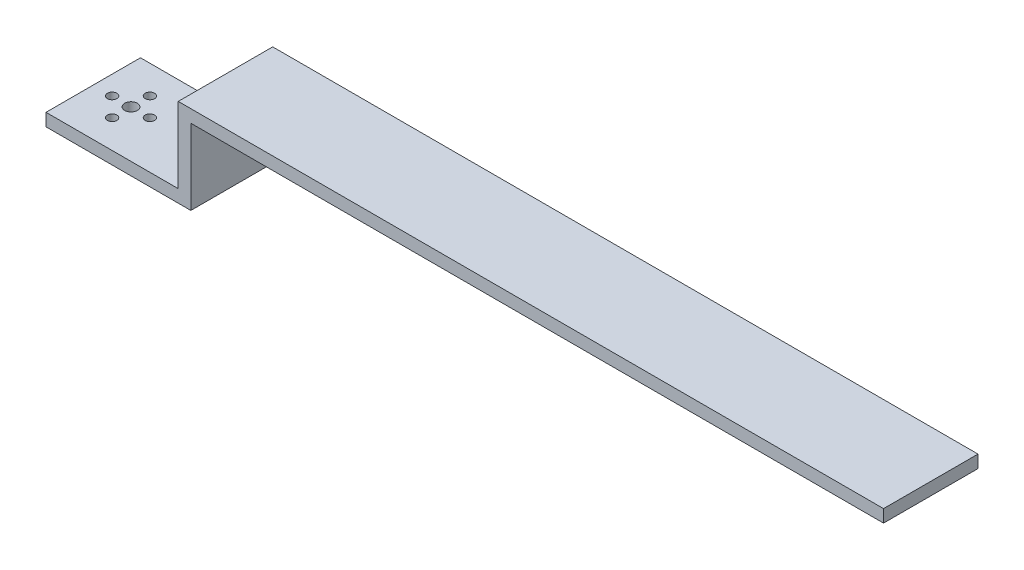
SolidWorks part; units mm, degrees
ref_plane "Front Plane" through (0, 0, 0) normal (0, 0, 1) x (1, 0, 0)
ref_plane "Top Plane" through (0, 0, 0) normal (0, 1, 0) x (1, 0, 0)
ref_plane "Right Plane" through (0, 0, 0) normal (1, 0, 0) x (0, 0, -1)
sketch "Sketch1" plane through (0, 0, 0) normal (0, 1, 0) x (1, 0, 0)
  line L0 (-23, 0) -> (23, 0) construction
  line L1 (-23, 15) -> (23, 15)
  line L2 (-23, 15) -> (-23, -15)
  line L3 (-23, -15) -> (23, -15)
  line L4 (23, 15) -> (23, -15)
  line L5 (-23, 15) -> (23, -15) construction
  line L6 (-23, -15) -> (23, 15) construction
  circle A0 centre (-11, 0) radius 6 construction
  circle A1 centre (-17, 0) radius 1.5
  circle A2 centre (-11, 6) radius 1.5
  circle A3 centre (-5, 0) radius 1.5
  circle A4 centre (-11, -6) radius 1.5
  circle A5 centre (-11, 0) radius 2
  point P0 (0, 0)
  point P9 (0, 0)
  point P22 (-11, 0)
  dimension "D3" = 12
  dimension "D4" = 12
  dimension "D5" = 3
  dimension "D6" = 4
  dimension "D7" = 4
  dimension "D1" = 30
  dimension "D2" = 46
extrude "Boss-Extrude1" add sketch "Sketch1" along normal blind 4
sketch "Sketch2" plane through (0, 4, 0) normal (0, 1, 0) x (1, 0, 0)
  line L0 (-23, -15) -> (23, -15) construction
  line L1 (23, 15) -> (19, 15)
  line L2 (23, 15) -> (23, -15)
  line L3 (23, -15) -> (19, -15)
  line L4 (19, 15) -> (19, -15)
  dimension "D1" = 4
extrude "Boss-Extrude2" add sketch "Sketch2" along normal blind 24
sketch "Sketch3" plane through (23, 0, 0) normal (1, 0, 0) x (0, 0, -1)
  line L0 (15, 28) -> (15, 0) construction
  line L1 (-15, 28) -> (15, 28)
  line L2 (-15, 28) -> (-15, 24)
  line L3 (-15, 24) -> (15, 24)
  line L4 (15, 28) -> (15, 24)
  dimension "D1" = 4
extrude "Boss-Extrude3" add sketch "Sketch3" along normal blind 220
